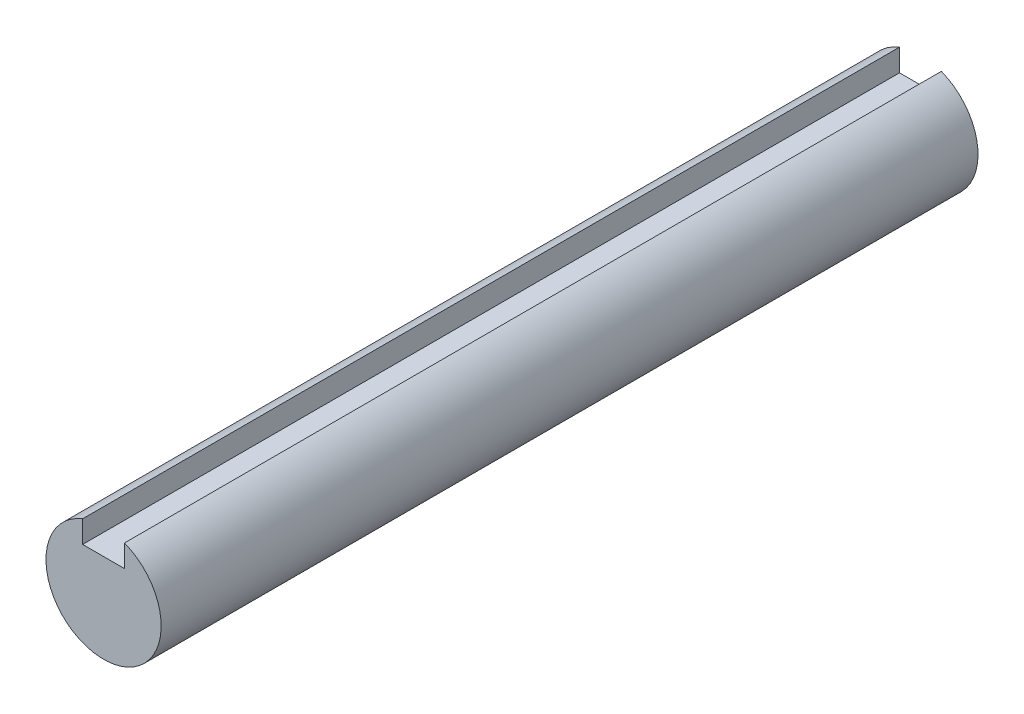
SolidWorks part; units mm, degrees
ref_plane "Front Plane" through (0, 0, 0) normal (0, 0, 1) x (1, 0, 0)
ref_plane "Top Plane" through (0, 0, 0) normal (0, 1, 0) x (1, 0, 0)
ref_plane "Right Plane" through (0, 0, 0) normal (1, 0, 0) x (0, 0, -1)
sketch "Sketch1" plane through (0, 0, 0) normal (0, 0, 1) x (1, 0, 0)
  line L1 (-2, 5.1235) -> (2, 5.1235)
  line L2 (-2, 5.1235) -> (-2, 3)
  line L3 (-2, 3) -> (2, 3)
  line L4 (2, 5.1235) -> (2, 3)
  circle A0 centre (0, 0) radius 5.5
  point P7 (0, 5.5)
  dimension "D1" = 11
  dimension "D2" = 2.5
  dimension "D3" = 4
extrude "Boss-Extrude1" add sketch "Sketch1" along normal blind 78 contours L2 A0 L4 L3
